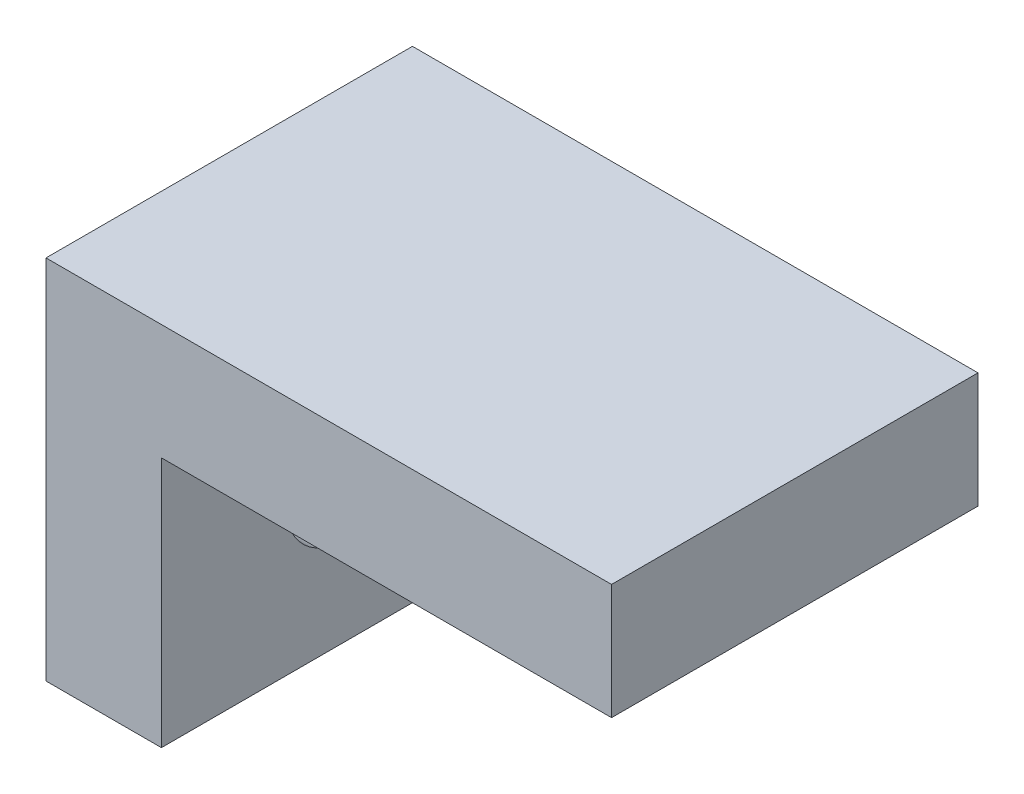
SolidWorks part; units mm, degrees
ref_plane "Front Plane" through (0, 0, 0) normal (0, 0, 1) x (1, 0, 0)
ref_plane "Top Plane" through (0, 0, 0) normal (0, 1, 0) x (1, 0, 0)
ref_plane "Right Plane" through (0, 0, 0) normal (1, 0, 0) x (0, 0, -1)
sketch "Sketch2" plane through (0, 0, 0) normal (0, 0, 1) x (1, 0, 0)
  line L0 (2.5, 7.9375) -> (2.5, 2.9375) construction
  line L5 (-2.5, 7.9375) -> (2.5, 7.9375)
  line L6 (-2.5, 7.9375) -> (-2.5, -7.9375)
  line L7 (-2.5, -7.9375) -> (2.5, -7.9375)
  line L8 (2.5, 2.9375) -> (2.5, -7.9375)
  line L9 (-2.5, 7.9375) -> (2.5, -7.9375) construction
  line L10 (-2.5, -7.9375) -> (2.5, 7.9375) construction
  line L11 (2.5, 7.9375) -> (22, 7.9375)
  line L12 (2.5, 7.9375) -> (2.5, 2.9375) construction
  line L13 (2.5, 2.9375) -> (22, 2.9375)
  line L14 (22, 7.9375) -> (22, 2.9375)
  point P0 (0, 0)
  dimension "D1" = 5
  dimension "D2" = 15.875
  dimension "D3" = 24.5
  dimension "D4" = 5
extrude "Boss-Extrude1" add sketch "Sketch2" along normal mid plane 15.875 contours L8 L7 L6 L5 L11 L14 L13
sketch "Sketch7" plane through (2.5, 0, 0) normal (1, 0, 0) x (0, 0, -1)
  line L3 (-7.9375, 4.8125) -> (7.9375, -7.9375) construction
  line L5 (7.9375, 4.8125) -> (-7.9375, -7.9375) construction
  line L8 (-7.9375, 2.9375) -> (-7.9375, -7.9375) construction
  line L9 (7.9375, 2.9375) -> (7.9375, -7.9375) construction
  line L10 (-7.9375, 2.9375) -> (7.9375, 2.9375) construction
  point P13 (0, -1.5625)
  point P40 (0, -1.5625)
  dimension "D1" = 4.5
hole_wizard "#10 Clearance Hole1" positions "Sketch7" profile "Sketch4" hole size "#10" standard "ANSI Inch" end condition up to next
sketch "Sketch4" plane through (2.5, -1.5625, 0) normal (0, 1, 0) x (0, 0, -1)
  line L0 (0, 0) -> (0, 5)
  line L1 (0, 5) -> (2.5527, 5)
  line L2 (2.5527, 5) -> (2.5527, 0)
  line L5 (2.5527, 0) -> (0, 0)
  line L11 (0, -6.35) -> (0, 107.95) construction
  dimension "Thru Hole Dia." = 5.1054
  dimension "Thru Hole Depth" = 5
sketch "Sketch6" plane through (0, 7.9375, 0) normal (0, 1, 0) x (1, 0, 0)
  line L0 (-2.5, 0) -> (-29.475, 0) construction
  line L1 (-2.5, -7.9375) -> (-2.5, 7.9375) construction
  dimension "D1" = 26.975
